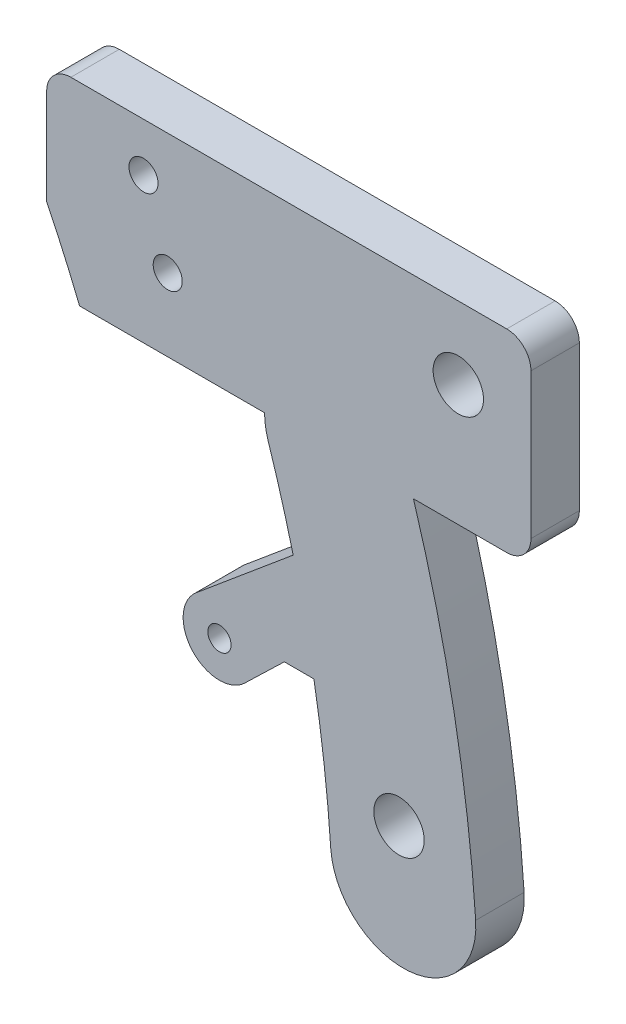
SolidWorks part; units mm, degrees
ref_plane "Front Plane" through (0, 0, 0) normal (0, 0, 1) x (1, 0, 0)
ref_plane "Top Plane" through (0, 0, 0) normal (0, 1, 0) x (1, 0, 0)
ref_plane "Right Plane" through (0, 0, 0) normal (1, 0, 0) x (0, 0, -1)
sketch "Sketch1" plane through (0, 0, 0) normal (0, 0, 1) x (1, 0, 0)
  line L0 (175.0574, 57.15) -> (141.7587, 55.9484)
  line L1 (175.0574, 57.15) -> (194.9977, 57.15)
  line L2 (-50.8, 0) -> (-50.8, -101.6)
  line L3 (-50.8, -101.6) -> (175.9764, -101.6)
  line L4 (0, 0) -> (161.27, -88.9) construction
  line L5 (0, 0) -> (176.6887, -51.8875) construction
  line L6 (136.9574, 55.7752) -> (-1.8319, 50.767)
  line L7 (136.9574, 82.55) -> (200.4574, 82.55)
  line L8 (136.9574, 82.55) -> (136.9574, 66.8463)
  line L9 (141.2786, 57.15) -> (200.4574, 57.15)
  line L10 (200.4574, 82.55) -> (200.4574, 57.15)
  circle A0 centre (0, 0) radius 50.8
  arc A1 (153.586, -101.6) -> (175.0574, 57.15) centre (0, 0) ccw
  arc A2 (175.9764, -101.6) -> (194.9977, 57.15) centre (0, 0) ccw
  arc A3 (130.1363, -101.6) -> (142.9808, 82.55) centre (0, 0) ccw
  circle A4 centre (161.27, -88.9) radius 3.302
  circle A5 centre (176.6887, -51.8875) radius 3.302
  circle A6 centre (183.731, -12.4151) radius 3.302
  circle A7 centre (183.162, 19.05) radius 3.302
  arc A8 (142.0258, -101.6) -> (153.8811, 82.55) centre (0, 0) ccw
  arc A9 (164.8862, -101.6) -> (175.2013, 82.55) centre (0, 0) ccw
  arc A10 (174.2092, 12.0431) -> (193.2139, 13.3569) centre (183.7115, 12.7) ccw
  arc A11 (184.1121, 60.106) -> (166.0027, 54.194) centre (175.0574, 57.15) ccw
  circle A12 centre (190.9324, 73.025) radius 3.302
  arc A13 (113.5923, -101.6) -> (136.9574, 66.8463) centre (0, 0) ccw
  dimension "D1" = 101.6
  dimension "D2" = 368.3
  dimension "D3" = 406.4
  dimension "D7" = 330.2
  dimension "D8" = 6.604
  dimension "D12" = 9.525
  dimension "D13" = 9.525
  dimension "D15" = 25.4
  dimension "D17" = 38.1
  dimension "D19" = 6.604
  dimension "D22" = 304.8
  dimension "D23" = 6.604
  dimension "D4" = 57.15
  dimension "D5" = 101.6
  dimension "D6" = 50.8
  dimension "D9" = 12.7
  dimension "D11" = 12.5
  dimension "D14" = 44.45
  dimension "D16" = 0
  dimension "D18" = 25.4
  dimension "D20" = 9.525
  dimension "D21" = 9.525
  dimension "D24" = 38.1
  dimension "D10" = 3
extrude "Boss-Extrude1" add sketch "Sketch1" along normal blind 6.35 contours A13 L9 A3 L7 L8 | L9 A8 L7 A3 | A11 A9 L7 A8 L9 | A9 L9 L10 L7 A12 | A9 A11 L9 L1 | A1 A10 A9 L1 A7 | L0 A11 A8 A10 A1 A7 | L9 A11 L0
fillet "Fillet1" radius 3.175 3 edges at (200.4574, 57.15, 3.175) (200.4574, 82.55, 3.175) (136.9574, 82.55, 3.175)
sketch "Sketch2" plane through (0, 0, 6.35) normal (0, 0, 1) x (1, 0, 0)
  line L5 (185.051, 57.15) -> (197.2824, 57.15)
  line L6 (200.4574, 60.325) -> (200.4574, 79.375)
  line L7 (197.2824, 82.55) -> (140.1324, 82.55)
  line L8 (136.9574, 79.375) -> (136.9574, 66.8463)
  line L9 (141.2786, 57.15) -> (165.5324, 57.15)
  line L10 (185.051, 57.15) -> (197.2824, 57.15)
  line L11 (200.4574, 60.325) -> (200.4574, 79.375)
  line L12 (197.2824, 82.55) -> (140.1324, 82.55)
  line L13 (136.9574, 79.375) -> (136.9574, 66.8463)
  line L14 (141.2786, 57.15) -> (165.5324, 57.15)
  circle A0 centre (149.6574, 76.2) radius 1.905
  circle A1 centre (152.8324, 66.675) radius 1.905
  arc A7 (197.2824, 57.15) -> (200.4574, 60.325) centre (197.2824, 60.325) ccw
  arc A8 (200.4574, 79.375) -> (197.2824, 82.55) centre (197.2824, 79.375) ccw
  arc A9 (140.1324, 82.55) -> (136.9574, 79.375) centre (140.1324, 79.375) ccw
  arc A12 (141.2786, 57.15) -> (136.9574, 66.8463) centre (0, 0) ccw
  arc A13 (174.2092, 12.0431) -> (166.0027, 54.194) centre (0, 0) ccw
  arc A14 (197.2824, 57.15) -> (200.4574, 60.325) centre (197.2824, 60.325) ccw
  arc A15 (200.4574, 79.375) -> (197.2824, 82.55) centre (197.2824, 79.375) ccw
  arc A16 (140.1324, 82.55) -> (136.9574, 79.375) centre (140.1324, 79.375) ccw
  arc A17 (141.2786, 57.15) -> (136.9574, 66.8463) centre (0, 0) ccw
  arc A18 (174.2092, 12.0431) -> (166.0027, 54.194) centre (0, 0) ccw
  arc A34 (165.5324, 57.15) -> (166.0027, 54.194) centre (175.0574, 57.15) ccw
  arc A35 (165.5324, 57.15) -> (166.0027, 54.194) centre (175.0574, 57.15) ccw
  arc A36 (174.2092, 12.0431) -> (193.2139, 13.3569) centre (183.7115, 12.7) ccw
  arc A37 (174.2092, 12.0431) -> (193.2139, 13.3569) centre (183.7115, 12.7) ccw
  arc A38 (193.2139, 13.3569) -> (185.051, 57.15) centre (0, 0) ccw
  arc A39 (193.2139, 13.3569) -> (185.051, 57.15) centre (0, 0) ccw
  dimension "D2" = 3.81
  dimension "D3" = 3.81
  dimension "D4" = 12.7
  dimension "D5" = 15.875
  dimension "D6" = 9.525
  dimension "D7" = 6.35
  dimension "D1" = 0
extrude "Cut-Extrude2" cut sketch "Sketch2" against normal up to surface (6.35 mm away) contours A0 | A1 up to face at (186.464, 19.05, 0)
sketch "Sketch3" plane through (0, 0, 6.35) normal (0, 0, 1) x (1, 0, 0)
  line L1 (168.1215, 30.1625) -> (172.0003, 30.1625)
  line L2 (169.2829, 42.8625) -> (156.5613, 32.2291)
  line L3 (171.4132, 33.3375) -> (162.9219, 25.1472)
  line L5 (185.051, 57.15) -> (197.2824, 57.15)
  line L6 (200.4574, 60.325) -> (200.4574, 79.375)
  line L7 (197.2824, 82.55) -> (140.1324, 82.55)
  line L8 (136.9574, 79.375) -> (136.9574, 66.8463)
  line L9 (141.2786, 57.15) -> (165.5324, 57.15)
  line L10 (185.051, 57.15) -> (197.2824, 57.15)
  line L11 (200.4574, 60.325) -> (200.4574, 79.375)
  line L12 (197.2824, 82.55) -> (140.1324, 82.55)
  line L13 (136.9574, 79.375) -> (136.9574, 66.8463)
  line L14 (141.2786, 57.15) -> (165.5324, 57.15)
  arc A0 (156.5613, 32.2291) -> (162.9219, 25.1472) centre (159.6156, 28.575) ccw
  circle A1 centre (159.6156, 28.575) radius 1.524
  arc A2 (160.2292, 29.97) -> (159.0867, 27.1457) centre (183.162, 19.05) ccw
  arc A3 (158.2514, 24.0121) -> (169.8239, 40.6661) centre (183.162, 19.05) ccw
  arc A4 (174.2092, 12.0431) -> (166.0027, 54.194) centre (0, 0) ccw construction
  circle A5 centre (190.9324, 73.025) radius 3.302
  circle A6 centre (190.9324, 73.025) radius 3.302
  circle A7 centre (183.162, 19.05) radius 3.302
  circle A8 centre (183.162, 19.05) radius 3.302
  circle A9 centre (149.6574, 76.2) radius 1.905
  circle A10 centre (149.6574, 76.2) radius 1.905
  circle A11 centre (152.8324, 66.675) radius 1.905
  circle A12 centre (152.8324, 66.675) radius 1.905
  arc A20 (197.2824, 57.15) -> (200.4574, 60.325) centre (197.2824, 60.325) ccw
  arc A21 (200.4574, 79.375) -> (197.2824, 82.55) centre (197.2824, 79.375) ccw
  arc A22 (140.1324, 82.55) -> (136.9574, 79.375) centre (140.1324, 79.375) ccw
  arc A23 (141.2786, 57.15) -> (136.9574, 66.8463) centre (0, 0) ccw
  arc A24 (165.5324, 57.15) -> (166.0027, 54.194) centre (175.0574, 57.15) ccw
  arc A25 (174.2092, 12.0431) -> (166.0027, 54.194) centre (0, 0) ccw
  arc A26 (174.2092, 12.0431) -> (193.2139, 13.3569) centre (183.7115, 12.7) ccw
  arc A27 (193.2139, 13.3569) -> (185.051, 57.15) centre (0, 0) ccw
  arc A28 (197.2824, 57.15) -> (200.4574, 60.325) centre (197.2824, 60.325) ccw
  arc A29 (200.4574, 79.375) -> (197.2824, 82.55) centre (197.2824, 79.375) ccw
  arc A30 (140.1324, 82.55) -> (136.9574, 79.375) centre (140.1324, 79.375) ccw
  arc A31 (141.2786, 57.15) -> (136.9574, 66.8463) centre (0, 0) ccw
  arc A32 (165.5324, 57.15) -> (166.0027, 54.194) centre (175.0574, 57.15) ccw
  arc A33 (174.2092, 12.0431) -> (166.0027, 54.194) centre (0, 0) ccw
  arc A34 (174.2092, 12.0431) -> (193.2139, 13.3569) centre (183.7115, 12.7) ccw
  arc A35 (193.2139, 13.3569) -> (185.051, 57.15) centre (0, 0) ccw
  dimension "D6" = 9.525
  dimension "D7" = 50.8
  dimension "D9" = 3.175
  dimension "D10" = 1.5875
  dimension "D13" = 3.048
  dimension "D8" = 9.525
  dimension "D12" = 1.5875
  dimension "D15" = 9.525
  dimension "D1" = 0
  dimension "D2" = 0
  dimension "D3" = 0
  dimension "D4" = 0
  dimension "D5" = 0
extrude "Boss-Extrude2" add sketch "Sketch3" against normal up to surface (6.35 mm away)
